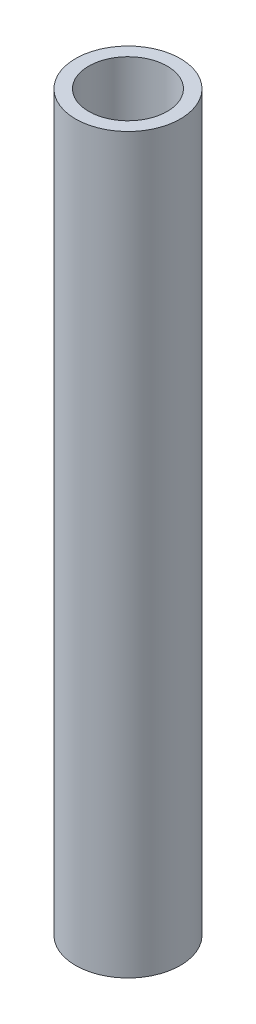
SolidWorks part; units mm, degrees
material "Delrin 2700 NC010, Low Viscosity Acetal Copolymer (SS)"
ref_plane "Front Plane" through (0, 0, 0) normal (0, 0, 1) x (1, 0, 0)
ref_plane "Top Plane" through (0, 0, 0) normal (0, 1, 0) x (1, 0, 0)
ref_plane "Right Plane" through (0, 0, 0) normal (1, 0, 0) x (0, 0, -1)
sketch "Sketch1" plane through (0, 0, 0) normal (0, 1, 0) x (1, 0, 0)
  circle A0 centre (0, 0) radius 9.525
  circle A1 centre (0, 0) radius 12.7
  dimension "D1" = 25.4
  dimension "D2" = 19.05
extrude "Boss-Extrude1" add sketch "Sketch1" along normal blind 177.8
